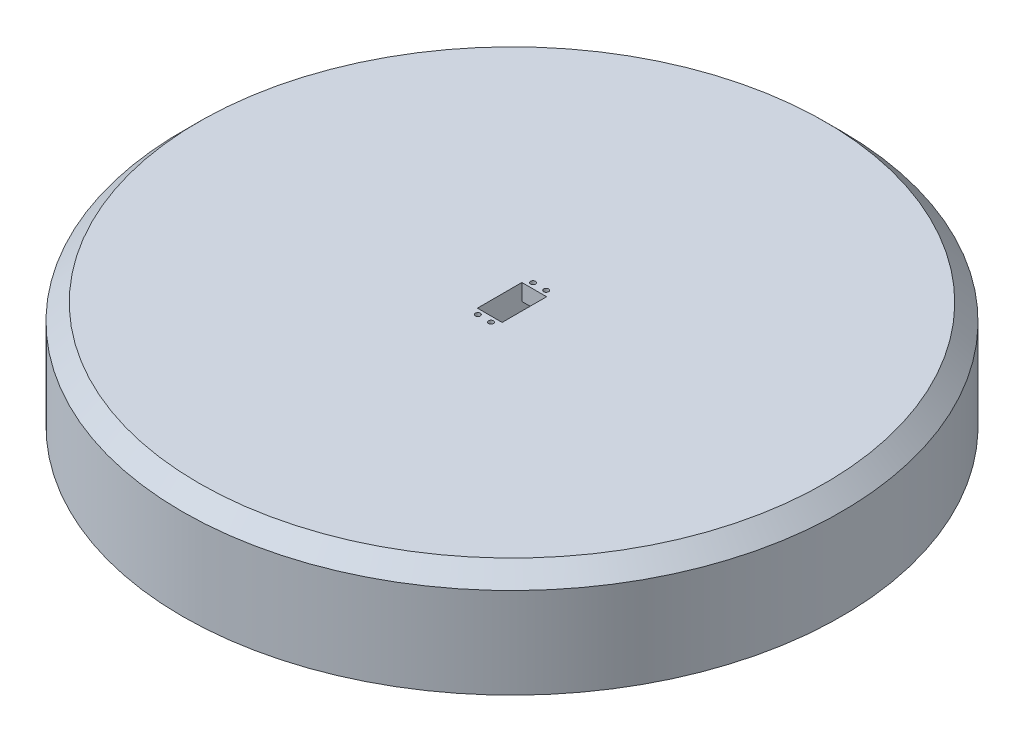
SolidWorks part; units mm, degrees
ref_plane "Front Plane" through (0, 0, 0) normal (0, 0, 1) x (1, 0, 0)
ref_plane "Top Plane" through (0, 0, 0) normal (0, 1, 0) x (1, 0, 0)
ref_plane "Right Plane" through (0, 0, 0) normal (1, 0, 0) x (0, 0, -1)
sketch "Sketch1" plane through (0, 0, 0) normal (0, 1, 0) x (1, 0, 0)
  circle A0 centre (0, 0) radius 200
  dimension "D1" = 400
extrude "Boss-Extrude1" add sketch "Sketch1" along normal blind 65
sketch "Sketch2" plane through (0, 65, 0) normal (0, 1, 0) x (1, 0, 0)
  line L0 (0, 200) -> (0, -200) construction
  line L2 (-7.5, 13.5) -> (7.5, 13.5)
  line L3 (-7.5, 13.5) -> (-7.5, -13.5)
  line L4 (-7.5, -13.5) -> (7.5, -13.5)
  line L5 (7.5, 13.5) -> (7.5, -13.5)
  line L6 (-7.5, 13.5) -> (7.5, -13.5) construction
  line L7 (-7.5, -13.5) -> (7.5, 13.5) construction
  circle A0 centre (0, 0) radius 200 construction
  point P5 (0, 0)
  point P10 (0, 0)
  dimension "D1" = 27
  dimension "D2" = 15
extrude "Cut-Extrude1" cut sketch "Sketch2" against normal through all
sketch "Sketch3" plane through (0, 0, 0) normal (0, -1, 0) x (1, 0, 0)
  line L1 (-7.5, 20) -> (7.5, 20)
  line L2 (-7.5, 20) -> (-7.5, -20)
  line L3 (-7.5, -20) -> (7.5, -20)
  line L4 (7.5, 20) -> (7.5, -20)
  line L5 (-7.5, 20) -> (7.5, -20) construction
  line L6 (-7.5, -20) -> (7.5, 20) construction
  point P0 (0, 0)
  dimension "D1" = 15
  dimension "D2" = 40
extrude "Cut-Extrude2" cut sketch "Sketch3" against normal offset from surface (55 mm away) 10 up to face at (0, 65, 0)
chamfer "Chamfer1" distance 10 1 edges at (0, 65, 200)
sketch "Sketch4" plane through (0, 55, 0) normal (0, -1, 0) x (-1, 0, 0)
  line L0 (7.5, -16.75) -> (-7.5, -16.75) construction
  line L1 (7.5, -20) -> (7.5, -13.5) construction
  line L2 (-7.5, -20) -> (-7.5, 20) construction
  line L3 (7.5, 16.75) -> (-7.5, 16.75) construction
  line L4 (7.5, 13.5) -> (7.5, 20) construction
  line L5 (0, 20) -> (0, -20) construction
  line L6 (7.5, 20) -> (-7.5, 20) construction
  line L7 (-7.5, -20) -> (7.5, -20) construction
  line L8 (-7.5, 0) -> (11.8781, 0) construction
  circle A0 centre (4, -16.75) radius 1.5
  circle A1 centre (-4, -16.75) radius 1.5
  circle A2 centre (4, 16.75) radius 1.5
  circle A3 centre (-4, 16.75) radius 1.5
  point P18 (0, -16.75)
  dimension "D1" = 3
  dimension "D2" = 4
extrude "Cut-Extrude3" cut sketch "Sketch4" against normal through all contours A3 | A2 | A0 | A1
sketch "Sketch5" plane through (0, 65, 0) normal (0, 1, 0) x (1, 0, 0)
  circle A0 centre (0, 0) radius 3.75
  dimension "D1" = 7.5
